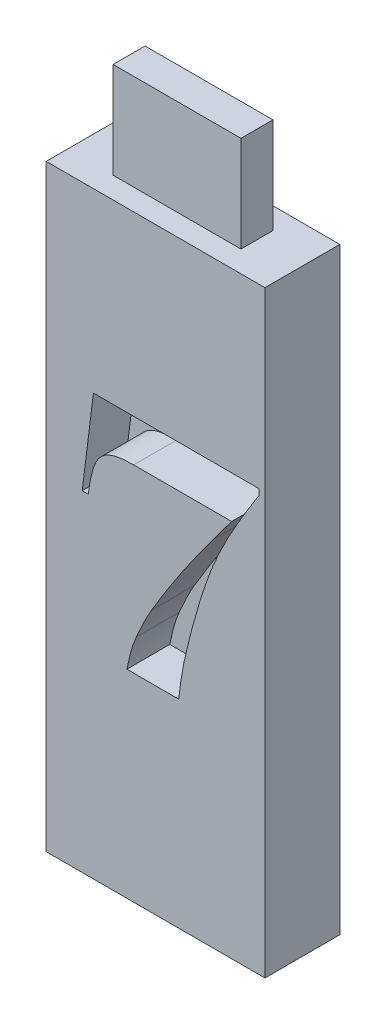
SolidWorks part; units mm, degrees
ref_plane "Front Plane" through (0, 0, 0) normal (0, 0, 1) x (1, 0, 0)
ref_plane "Top Plane" through (0, 0, 0) normal (0, 1, 0) x (1, 0, 0)
ref_plane "Right Plane" through (0, 0, 0) normal (1, 0, 0) x (0, 0, -1)
sketch "Sketch1" plane through (0, 0, 0) normal (0, 0, 1) x (1, 0, 0)
  line L1 (-8.69, -23.749) -> (8.69, -23.749)
  line L2 (-8.69, -23.749) -> (-8.69, 23.749)
  line L3 (-8.69, 23.749) -> (8.69, 23.749)
  line L4 (8.69, -23.749) -> (8.69, 23.749)
  line L5 (-8.69, -23.749) -> (8.69, 23.749) construction
  line L6 (-8.69, 23.749) -> (8.69, -23.749) construction
  point P0 (0, 0)
  dimension "D1" = 17.38
  dimension "D2" = 47.498
extrude "Boss-Extrude1" add sketch "Sketch1" along normal blind 5.95
sketch "Sketch2" plane through (0, 0, 5.95) normal (0, 0, 1) x (1, 0, 0)
  line L0 (0, 23.749) -> (0, -23.749) construction
  line L1 (8.69, 23.749) -> (-8.69, 23.749) construction
  line L2 (-8.69, -23.749) -> (8.69, -23.749) construction
  line L3 (0, -23.749) -> (0, 0) construction
  line L4 (0, 0) -> (-8.69, 0) construction
  line L5 (-8.69, 23.749) -> (-8.69, -23.749) construction
  line L6 (-8.69, 0) -> (8.69, 0) construction
  line L7 (8.69, -23.749) -> (8.69, 23.749) construction
  line L8 (-8.69, -23.749) -> (8.69, -23.749) construction
  line L9 (-8.69, -21.209) -> (8.69, -21.209) construction
  line L10 (-8.69, -18.669) -> (8.69, -18.669) construction
  line L11 (-8.69, -16.129) -> (8.69, -16.129) construction
  line L12 (-8.69, -13.589) -> (8.69, -13.589) construction
  line L13 (-8.69, -11.049) -> (8.69, -11.049) construction
  line L14 (-8.69, -8.509) -> (8.69, -8.509) construction
  line L15 (-8.69, -5.969) -> (8.69, -5.969) construction
  line L16 (-8.69, -3.429) -> (8.69, -3.429) construction
  line L17 (-8.69, -0.889) -> (8.69, -0.889) construction
  line L18 (-8.69, 1.651) -> (8.69, 1.651) construction
  line L19 (-8.69, 4.191) -> (8.69, 4.191) construction
  line L20 (-8.69, 6.731) -> (8.69, 6.731) construction
  line L21 (-8.69, 9.271) -> (8.69, 9.271) construction
  line L22 (-8.69, 11.811) -> (8.69, 11.811) construction
  line L23 (-8.69, 14.351) -> (8.69, 14.351) construction
  line L24 (-8.69, 16.891) -> (8.69, 16.891) construction
  line L25 (-8.69, 19.431) -> (8.69, 19.431) construction
  line L26 (-8.69, 21.971) -> (8.69, 21.971) construction
  line L27 (-8.69, 23.749) -> (-8.69, -23.749) construction
  line L28 (-6.15, 23.749) -> (-6.15, -23.749) construction
  line L29 (-3.61, 23.749) -> (-3.61, -23.749) construction
  line L30 (-1.07, 23.749) -> (-1.07, -23.749) construction
  line L31 (1.47, 23.749) -> (1.47, -23.749) construction
  line L32 (4.01, 23.749) -> (4.01, -23.749) construction
  line L33 (6.55, 23.749) -> (6.55, -23.749) construction
  text T0 "7\r\n" font "Engravers MT" height in points 72
  dimension "D1" = 19
  dimension "D2" = 2.54
  dimension "D4" = 2.54
  dimension "D3" = 7
extrude "Cut-Extrude1" cut sketch "Sketch2" against normal blind 3.41
sketch "Sketch3" plane through (0, 23.749, 0) normal (0, 1, 0) x (1, 0, 0)
  line L0 (0, 0) -> (0, -5.95) construction
  line L1 (8.69, -5.95) -> (-8.69, -5.95) construction
  line L2 (0, -5.95) -> (0, -2.975) construction
  line L3 (0, -2.975) -> (-8.69, -2.975) construction
  line L4 (-8.69, -5.95) -> (-8.69, 0) construction
  line L5 (-8.69, -2.975) -> (8.69, -2.975) construction
  line L6 (8.69, -5.95) -> (8.69, 0) construction
  line L8 (-5.08, -4.245) -> (5.08, -4.245)
  line L9 (-5.08, -4.245) -> (-5.08, -1.705)
  line L10 (-5.08, -1.705) -> (5.08, -1.705)
  line L11 (5.08, -4.245) -> (5.08, -1.705)
  line L12 (-5.08, -4.245) -> (5.08, -1.705) construction
  line L13 (-5.08, -1.705) -> (5.08, -4.245) construction
  dimension "D1" = 2.54
  dimension "D2" = 10.16
extrude "Boss-Extrude2" add sketch "Sketch3" along normal blind 7.62
